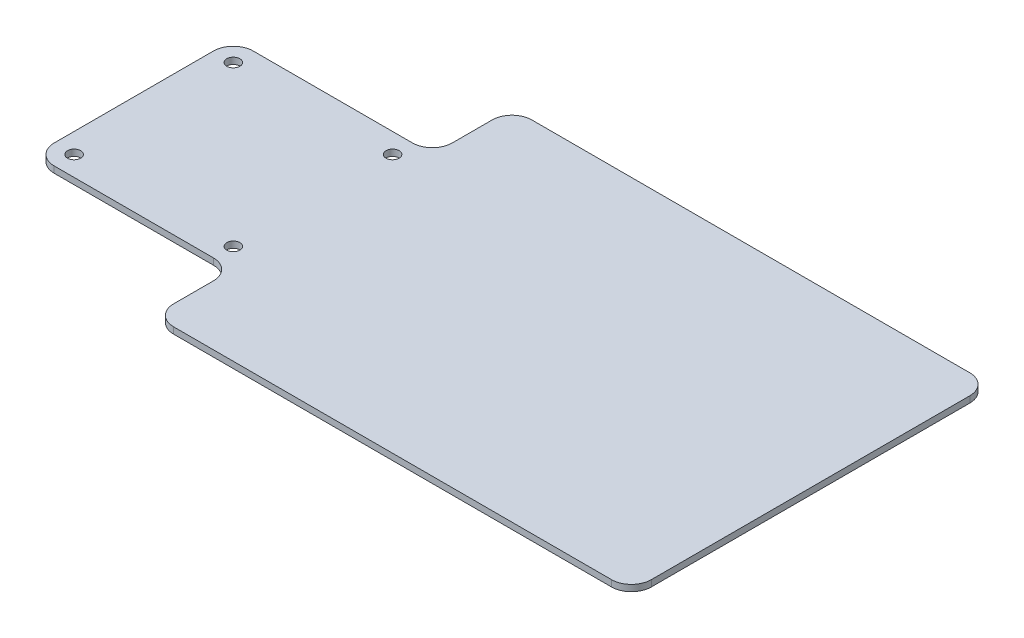
SolidWorks part; units mm, degrees
ref_plane "Front Plane" through (0, 0, 0) normal (0, 0, 1) x (1, 0, 0)
ref_plane "Top Plane" through (0, 0, 0) normal (0, 1, 0) x (1, 0, 0)
ref_plane "Right Plane" through (0, 0, 0) normal (1, 0, 0) x (0, 0, -1)
sketch "Sketch1" plane through (0, 0, 0) normal (0, 1, 0) x (1, 0, 0)
  line L0 (-25, 25) -> (25, 25)
  line L1 (25, 45) -> (145, 45)
  line L2 (-25, 25) -> (-25, -25)
  line L3 (25, -45) -> (145, -45)
  line L4 (145, 45) -> (145, -45)
  line L5 (25, 25) -> (25, 45)
  line L6 (-25, -25) -> (25, -25)
  line L7 (25, -25) -> (25, -45)
  dimension "D1" = 120
  dimension "D2" = 25
  dimension "D3" = 25
  dimension "D4" = 90
  dimension "D5" = 50
  dimension "D6" = 20
  dimension "D7" = 50
extrude "Boss-Extrude1" add sketch "Sketch1" along normal blind 1.6
fillet "Fillet1" radius 5 8 edges at (145, 0.8, -45) (145, 0.8, 45) (25, 0.8, -45) (25, 0.8, -25) (-25, 0.8, -25) (-25, 0.8, 25) (25, 0.8, 25) (25, 0.8, 45)
sketch "Sketch2" plane through (0, 1.6, 0) normal (0, 1, 0) x (1, 0, 0)
  line L0 (0, 20) -> (0, -20) construction
  line L1 (-20, 20) -> (20, 20) construction
  line L2 (-20, 20) -> (-20, -20) construction
  line L3 (-20, -20) -> (20, -20) construction
  line L4 (20, 20) -> (20, -20) construction
  circle A0 centre (-20, 20) radius 1.65
  circle A1 centre (20, 20) radius 1.65
  circle A2 centre (20, -20) radius 1.65
  circle A3 centre (-20, -20) radius 1.65
  dimension "D1" = 3.3
  dimension "D2" = 40
  dimension "D3" = 40
extrude "Cut-Extrude1" cut sketch "Sketch2" against normal through all
